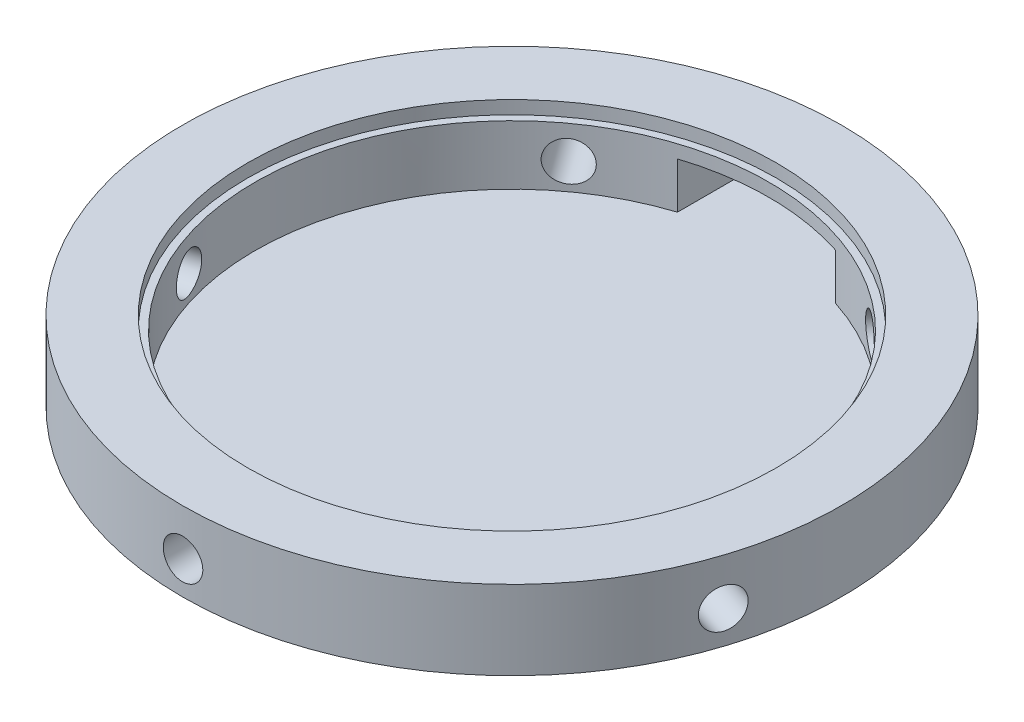
SolidWorks part; units mm, degrees
ref_plane "Front Plane" through (0, 0, 0) normal (0, 0, 1) x (1, 0, 0)
ref_plane "Top Plane" through (0, 0, 0) normal (0, 1, 0) x (1, 0, 0)
ref_plane "Right Plane" through (0, 0, 0) normal (1, 0, 0) x (0, 0, -1)
sketch "Sketch1" plane through (0, 0, 0) normal (0, 1, 0) x (1, 0, 0)
  circle A0 centre (0, 0) radius 50
  dimension "D1" = 100
extrude "Boss-Extrude1" add sketch "Sketch1" along normal blind 12
sketch "Sketch3" plane through (0, 12, 0) normal (0, 1, 0) x (1, 0, 0)
  circle A0 centre (0, 0) radius 40.1
  dimension "D1" = 80.2
extrude "Cut-Extrude1" cut sketch "Sketch3" against normal blind 2
sketch "Sketch4" plane through (0, 10, 0) normal (0, 1, 0) x (1, 0, 0)
  circle A0 centre (0, 0) radius 39
  dimension "D1" = 78
extrude "Cut-Extrude2" cut sketch "Sketch4" against normal blind 9
sketch "Sketch5" plane through (0, 1, 0) normal (0, 1, 0) x (1, 0, 0)
  line L0 (-6.6, 0) -> (6.6, 0) construction
  circle A0 centre (0, 0) radius 48
  dimension "D1" = 96
sketch "Sketch6" plane through (0, 0, 0) normal (0, 0, 1) x (1, 0, 0)
  line L0 (-12, 1) -> (12, 1)
  line L1 (48, 1) -> (-48, 1) construction
  line L2 (12, 1) -> (12, 8)
  line L3 (12, 8) -> (-12, 8)
  line L4 (0, 8) -> (0, 1) construction
  line L5 (-12, 1) -> (-12, 8)
  dimension "D1" = 12
  dimension "D2" = 7
extrude "Cut-Extrude4" cut sketch "Sketch6" against normal blind 61
ref_axis "Axis1" through (0, -0.6, 0) along (0, 1, 0)
ref_plane "Plane1" through (0, 0, 0) normal (1, 0, 0) x (0, 1, 0)
ref_plane "Plane2" through (0, 0, 0) normal (0, 0, -1) x (0, 1, 0)
sketch "Sketch7" plane through (0, 0, 0) normal (0, 0, -1) x (0, 1, 0)
  line L0 (7.26, 0) -> (-7.26, 0) construction
  line L1 (0, 50) -> (0, -50) construction
  circle A0 centre (5, 0) radius 3
  dimension "D1" = 6
  dimension "D2" = 5
extrude "Cut-Extrude5" cut sketch "Sketch7" against normal blind 61
pattern_circular "CirPattern1" count 5 over 360 about axis through (0, -0.6, 0) along (0, 1, 0) of "Cut-Extrude5"
